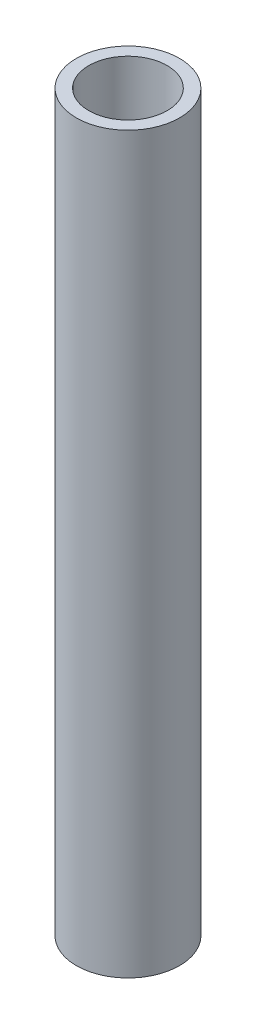
SolidWorks part; units mm, degrees
ref_plane "Front Plane" through (0, 0, 0) normal (0, 0, 1) x (1, 0, 0)
ref_plane "Top Plane" through (0, 0, 0) normal (0, 1, 0) x (1, 0, 0)
ref_plane "Right Plane" through (0, 0, 0) normal (1, 0, 0) x (0, 0, -1)
sketch "Sketch1" plane through (0, 0, 0) normal (0, 1, 0) x (1, 0, 0)
  circle A0 centre (0, 0) radius 1.054
  circle A1 centre (0, 0) radius 0.8
extrude "Boss-Extrude1" add sketch "Sketch1" along normal blind 15
